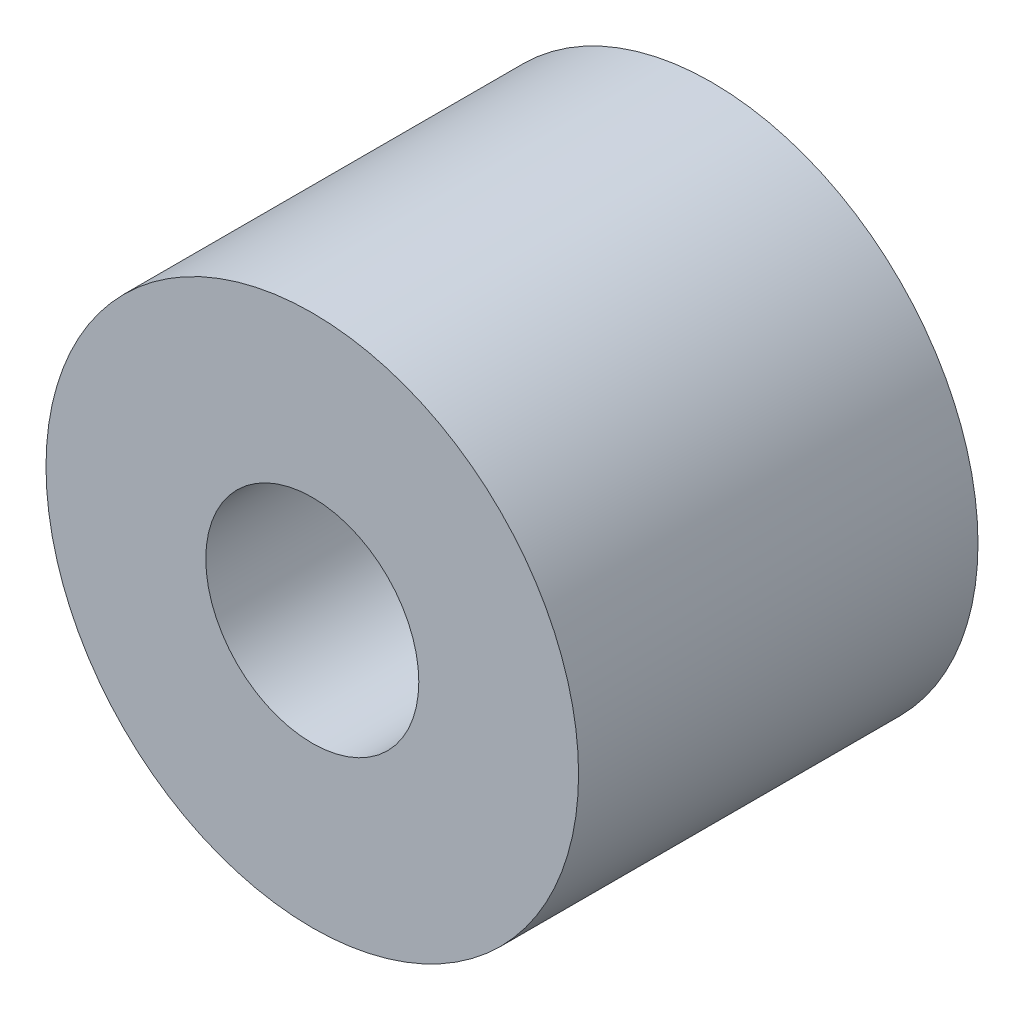
SolidWorks part; units mm, degrees
ref_plane "前视基准面" through (0, 0, 0) normal (0, 0, 1) x (1, 0, 0)
ref_plane "上视基准面" through (0, 0, 0) normal (0, 1, 0) x (1, 0, 0)
ref_plane "右视基准面" through (0, 0, 0) normal (1, 0, 0) x (0, 0, -1)
other "Configuration Table"
sketch "草图2" plane through (0, 0, 0) normal (0, 0, 1) x (1, 0, 0)
  circle A0 centre (0, 0) radius 10
extrude "凸台-拉伸1" add sketch "草图2" along normal blind 15
sketch "草图3" plane through (0, 0, 0) normal (0, 0, 1) x (1, 0, 0)
  circle A0 centre (0, 0) radius 4
extrude "切除-拉伸1" cut sketch "草图3" along normal blind 15
